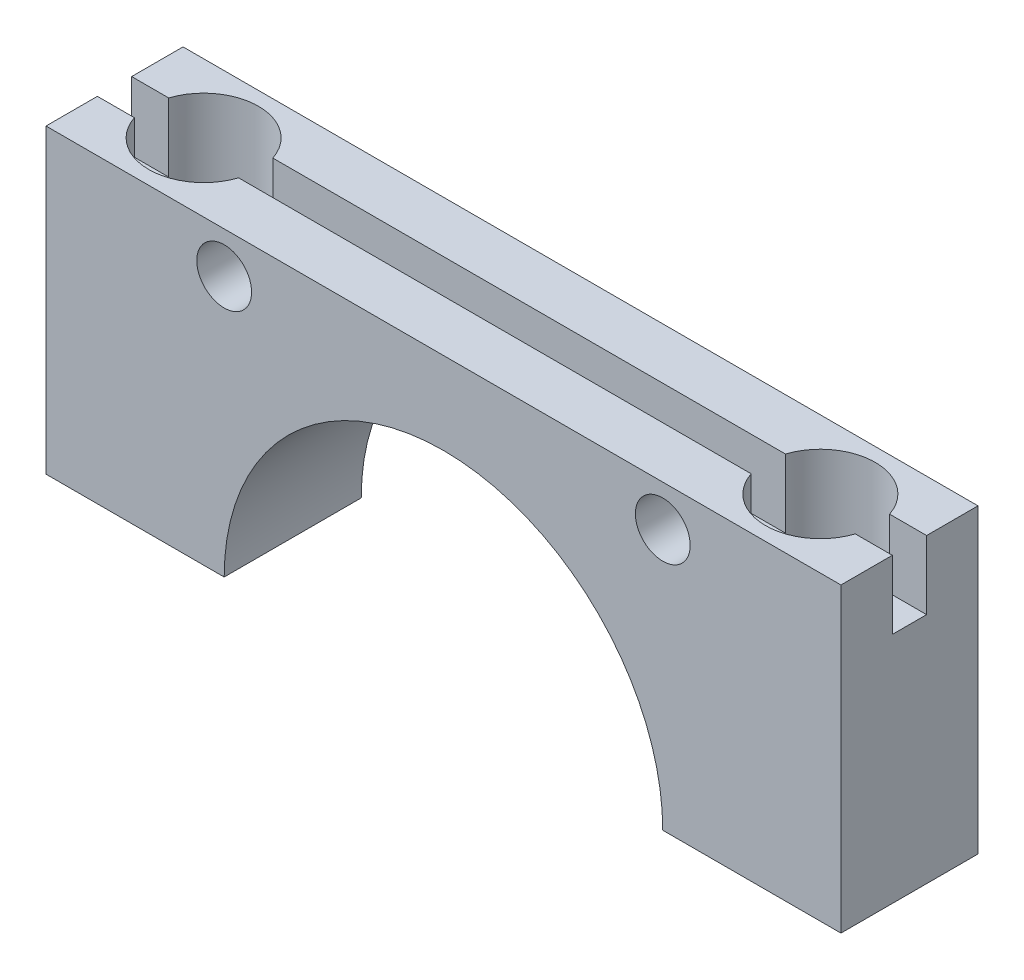
SolidWorks part; units mm, degrees
ref_plane "前视基准面" through (0, 0, 0) normal (0, 0, 1) x (1, 0, 0)
ref_plane "上视基准面" through (0, 0, 0) normal (0, 1, 0) x (1, 0, 0)
ref_plane "右视基准面" through (0, 0, 0) normal (1, 0, 0) x (0, 0, -1)
sketch "草图1" plane through (0, 0, 0) normal (0, 0, 1) x (1, 0, 0)
  line L0 (-69.3343, 6.5745) -> (-69.3343, 28.5745)
  line L2 (-69.3343, 8.5745) -> (-11.3343, 8.5745) construction
  line L3 (-69.3343, 8.5745) -> (-69.3343, 4.5745) construction
  line L4 (-69.3343, 4.5745) -> (-11.3343, 4.5745) construction
  line L5 (-11.3343, 8.5745) -> (-11.3343, 4.5745) construction
  line L8 (-69.3343, 6.5745) -> (-56.3343, 6.5745)
  line L10 (-11.3343, 6.5745) -> (-24.3343, 6.5745)
  line L11 (-69.3343, 28.5745) -> (-11.3343, 28.5745)
  line L12 (-11.3343, 28.5745) -> (-11.3343, 6.5745)
  circle A0 centre (-40.3343, 6.5745) radius 16 construction
  circle A1 centre (-40.3343, 6.5745) radius 19 construction
  arc A3 (-56.3343, 6.5745) -> (-24.3343, 6.5745) centre (-40.3343, 6.5745) cw
  point P9 (-69.3343, 6.5745)
  point P11 (-40.3343, 8.5745)
  dimension "D1" = 4
  dimension "D2" = 29
  dimension "D3" = 22
extrude "凸台-拉伸1" add sketch "草图1" along normal blind 10
sketch "草图2" plane through (0, 6.5745, 0) normal (0, -1, 0) x (1, 0, 0)
  line L0 (-69.3343, 10) -> (-56.3343, 10) construction
  line L1 (-69.3343, 10) -> (-69.3343, 0) construction
  line L2 (-24.3343, 10) -> (-11.3343, 10) construction
  line L3 (-11.3343, 10) -> (-11.3343, 0) construction
  circle A0 centre (-62.8343, 5) radius 1.8
  circle A1 centre (-17.8343, 5) radius 1.88
  point P0 (-62.8343, 10)
  point P1 (-69.3343, 5)
  point P4 (-17.8343, 10)
  point P7 (-11.3343, 5)
  point P10 (-62.8343, 5)
  point P13 (-17.8343, 5)
extrude "切除-拉伸1" cut sketch "草图2" against normal blind 27
sketch "草图3" plane through (0, 28.5745, 0) normal (0, 1, 0) x (1, 0, 0)
  circle A0 centre (-62.8343, -5) radius 4
  circle A1 centre (-17.8343, -5) radius 4
extrude "切除-拉伸2" cut sketch "草图3" against normal blind 15
sketch "草图4" plane through (0, 28.5745, 0) normal (0, 1, 0) x (1, 0, 0)
  line L0 (-69.3343, -10) -> (-69.3343, 0) construction
  line L1 (-69.3343, -3.75) -> (-11.3343, -3.75)
  line L2 (-69.3343, -3.75) -> (-69.3343, -6.25)
  line L3 (-69.3343, -6.25) -> (-11.3343, -6.25)
  line L4 (-11.3343, -3.75) -> (-11.3343, -6.25)
  line L5 (-11.3343, 0) -> (-69.3343, 0) construction
  point P4 (-69.3343, -5)
  point P5 (-69.3343, -5)
  point P6 (-40.3343, -3.75)
  point P9 (-40.3343, 0)
  point P10 (0, 0)
  point P13 (0, 0)
  dimension "D1" = 2.5
extrude "切除-拉伸4" cut sketch "草图4" against normal blind 5
sketch "草图5" plane through (0, 0, 10) normal (0, 0, 1) x (1, 0, 0)
  line L0 (-11.3343, 28.5745) -> (-69.3343, 28.5745) construction
  circle A0 centre (-56.3343, 25.5745) radius 2
  circle A1 centre (-24.3343, 25.5745) radius 2
  point P4 (0, 0)
  point P6 (0, 0)
  dimension "D1" = 3
  dimension "D2" = 3
extrude "切除-拉伸5" cut sketch "草图5" against normal blind 5
